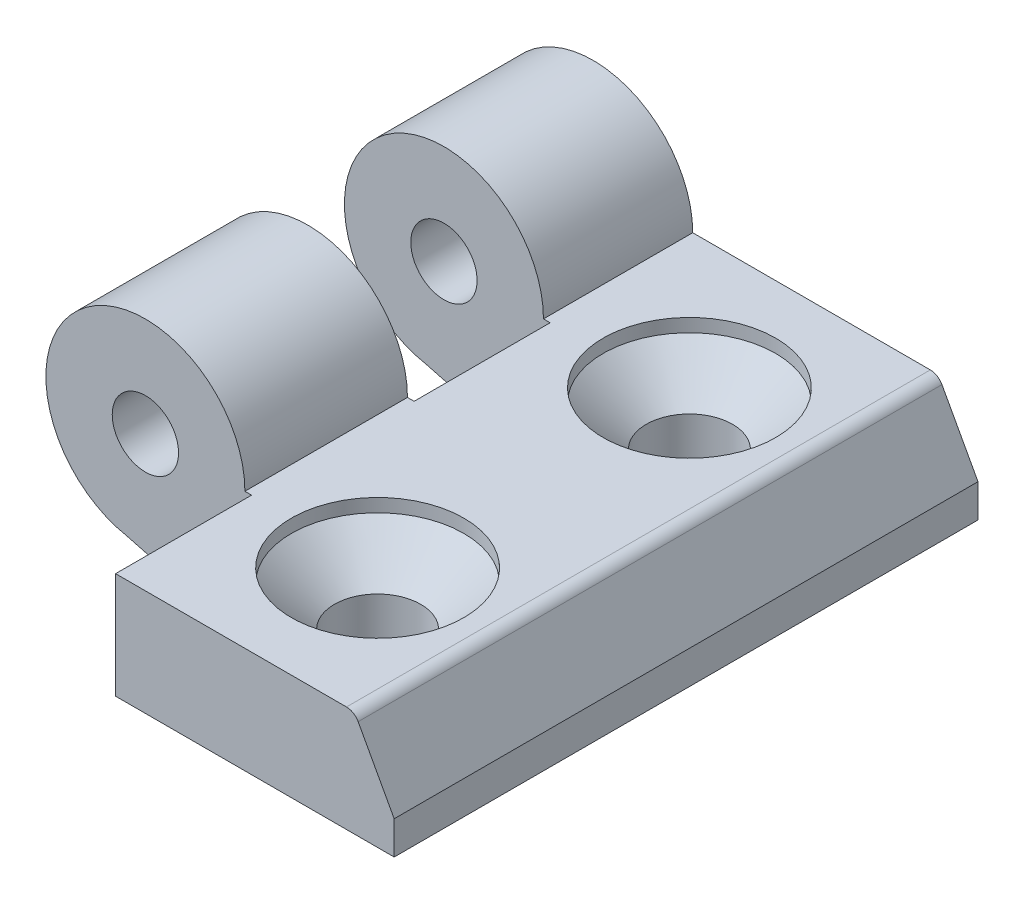
SolidWorks part; units mm, degrees
ref_plane "前视基准面" through (0, 0, 0) normal (0, 0, 1) x (1, 0, 0)
ref_plane "上视基准面" through (0, 0, 0) normal (0, 1, 0) x (1, 0, 0)
ref_plane "右视基准面" through (0, 0, 0) normal (1, 0, 0) x (0, 0, -1)
sketch "草图1" plane through (0, 0, 0) normal (0, 0, 1) x (1, 0, 0)
  line B0 (29, -5.5) -> (29, -8)
  line B1 (25.4064, 0) -> (7.5, 0)
  line B2 (29, -8) -> (1, -8)
  line B3 (29, -5.5) -> (26.2843, -0.5211)
  line B4 (1, -8) -> (-1.3701, -7.3738)
  arc B5 (7.5, 0) -> (-1.3701, -7.3738) centre (0, 0) ccw
  arc B6 (26.2843, -0.5211) -> (25.4064, 0) centre (25.4064, -1) ccw
sketch_block_instance "A$C603C625E-1"
sketch_block "A$C603C625E"
extrude "凸台-拉伸1" add sketch "草图1" along normal mid plane 44
ref_plane "基准面2" through (0, 0, 11.75) normal (0, 0, 1) x (1, 0, 0)
sketch "草图3" plane through (0, 0, 11.75) normal (0, 0, 1) x (1, 0, 0)
  line L2 (24, 0) -> (17.5, 0)
  line L10 (24, -1) -> (20.75, -4)
  line L11 (24, -1) -> (24, 0)
  line L12 (17.5, -8) -> (17.5, 0)
  line L13 (20.75, -4) -> (20.75, -8)
  line L14 (20.75, -8) -> (17.5, -8)
revolve "切除-旋转1" cut sketch "草图3" angle 360 about L12
pattern_linear "阵列(线性)1" count 2 spacing 23.5 along (0, 0, -1) of "切除-旋转1"
sketch "草图4" plane through (0, 0, 0) normal (0, 1, 0) x (1, 0, 0)
  line L0 (-25.4064, -22) -> (-7.5, -22) construction
  line L1 (-8.0973, -22) -> (8.0036, -22)
  line L2 (-8.0973, -22) -> (-8.0973, -11.75)
  line L3 (-8.0973, -11.75) -> (8.0036, -11.75)
  line L4 (8.0036, -22) -> (8.0036, -11.75)
  line L9 (-8.0973, 0.5) -> (8.0036, 0.5)
  line L10 (-8.0973, 0.5) -> (-8.0973, 10.75)
  line L11 (-8.0973, 10.75) -> (8.0036, 10.75)
  line L12 (8.0036, 0.5) -> (8.0036, 10.75)
  line L17 (-8.0973, 11.75) -> (8.0036, 11.75) [skipped]
  line L18 (-8.0973, 11.75) -> (-8.0973, 22) [skipped]
  line L19 (-8.0973, 22) -> (8.0036, 22) [skipped]
  line L20 (8.0036, 11.75) -> (8.0036, 22) [skipped]
  line L21 (-8.0973, -10.75) -> (8.0036, -10.75) [skipped]
  line L22 (-8.0973, -10.75) -> (-8.0973, -0.5) [skipped]
  line L23 (-8.0973, -0.5) -> (8.0036, -0.5) [skipped]
  line L24 (8.0036, -10.75) -> (8.0036, -0.5) [skipped]
  dimension "D1" = 10.25
  dimension "D2" = 4
extrude "切除-拉伸1" cut sketch "草图4" against normal through all and the other way through all
sketch "草图5" plane through (0, 0, -22) normal (0, 0, -1) x (-1, 0, 0)
  circle A0 centre (0, 0) radius 2.5
extrude "切除-拉伸2" cut sketch "草图5" against normal through all
